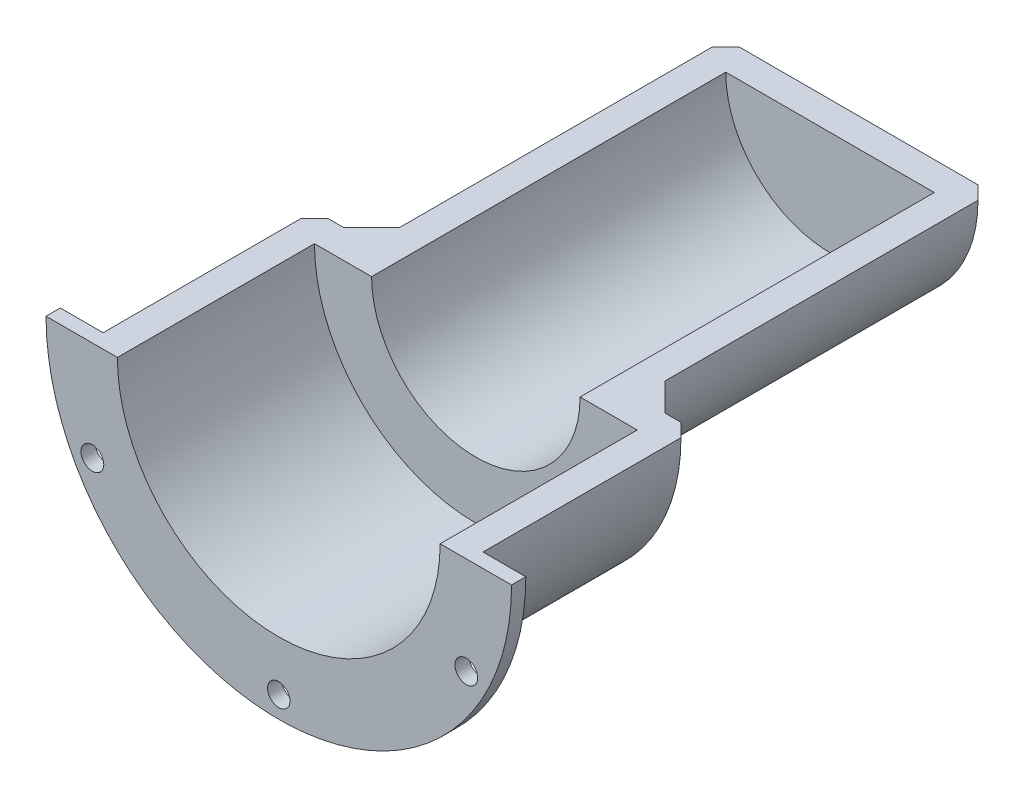
SolidWorks part; units mm, degrees
ref_plane "Front Plane" through (0, 0, 0) normal (0, 0, 1) x (1, 0, 0)
ref_plane "Top Plane" through (0, 0, 0) normal (0, 1, 0) x (1, 0, 0)
ref_plane "Right Plane" through (0, 0, 0) normal (1, 0, 0) x (0, 0, -1)
sketch "Sketch2" plane through (0, 0, 0) normal (0, 0, 1) x (1, 0, 0)
  line L0 (-23.622, 0) -> (23.622, 0) construction
  line L1 (-23.622, 0) -> (23.622, 0)
  arc A0 (-23.622, 0) -> (23.622, 0) centre (0, 0) ccw
  arc A1 (-18.542, 0) -> (18.542, 0) centre (0, 0) ccw
  arc A2 (18.542, 0) -> (-18.542, 0) centre (0, 0) ccw construction
  arc A3 (23.622, 0) -> (-23.622, 0) centre (0, 0) ccw construction
  dimension "D1" = 47.244
extrude "Boss-Extrude1" add sketch "Sketch2" against normal blind 62.992 contours A1 L1 A0
sketch "Sketch3" plane through (0, 0, 0) normal (0, 0, 1) x (1, 0, 0)
  line L0 (-23.622, 0) -> (23.622, 0) construction
  line L1 (-18.542, 0) -> (18.542, 0)
  arc A0 (-18.542, 0) -> (18.542, 0) centre (0, 0) ccw
extrude "Cut-Extrude1" cut sketch "Sketch3" against normal blind 57.912
sketch "Sketch5" plane through (0, 0, 0) normal (0, 0, 1) x (1, 0, 0)
  line L0 (-33.782, 0) -> (33.782, 0)
  arc A0 (-33.782, 0) -> (33.782, 0) centre (0, 0) ccw
extrude "Boss-Extrude2" add sketch "Sketch5" along normal blind 40.132
sketch "Sketch6" plane through (0, 0, 40.132) normal (0, 0, 1) x (1, 0, 0)
  line L0 (33.782, 0) -> (-33.782, 0) construction
  line L1 (-18.542, 0) -> (18.542, 0)
  arc A0 (-18.542, 0) -> (18.542, 0) centre (0, 0) ccw
extrude "Cut-Extrude2" cut sketch "Sketch6" against normal blind 40.132
sketch "Sketch7" plane through (0, 0, 40.132) normal (0, 0, 1) x (1, 0, 0)
  line L0 (-18.542, 0) -> (-33.782, 0) construction
  line L1 (33.782, 0) -> (18.542, 0) construction
  line L2 (-28.702, 0) -> (28.702, 0)
  arc A0 (-28.702, 0) -> (28.702, 0) centre (0, 0) ccw
extrude "Cut-Extrude3" cut sketch "Sketch7" against normal blind 35.052
sketch "Sketch9" plane through (0, 0, 40.132) normal (0, 0, 1) x (1, 0, 0)
  line L0 (-41.402, 0) -> (41.402, 0)
  arc A0 (-41.402, 0) -> (41.402, 0) centre (0, 0) ccw
extrude "Boss-Extrude3" add sketch "Sketch9" against normal blind 2.54
sketch "Sketch10" plane through (0, 0, 40.132) normal (0, 0, 1) x (1, 0, 0)
  line L0 (41.402, 0) -> (-41.402, 0) construction
  line L1 (-28.702, 0) -> (28.702, 0)
  arc A0 (-28.702, 0) -> (28.702, 0) centre (0, 0) ccw
extrude "Cut-Extrude4" cut sketch "Sketch10" against normal blind 2.54
chamfer "Chamfer1" distance 4.92 angle 45 1 edges at (0, -23.622, 0)
chamfer "Chamfer3" distance 2.38 angle 45 1 edges at (0, -23.622, -62.992)
chamfer "Chamfer4" distance 2.38 angle 45 1 edges at (0, -33.782, 0)
sketch "Sketch12" plane through (0, 0, 37.592) normal (0, 0, -1) x (-1, 0, 0)
  circle A0 centre (0, -37.592) radius 2
  arc A2 (-33.782, 0) -> (33.782, 0) centre (0, 0) ccw construction
  point P12 (0, -33.782)
  dimension "D1" = 3.81
  dimension "D2" = 4
extrude "Cut-Extrude6" cut sketch "Sketch12" against normal blind 2.54
sketch "Sketch16" plane through (0, 0, 40.132) normal (0, 0, 1) x (1, 0, 0)
  circle A0 centre (-33.1564, -17.7147) radius 2.032
  circle A1 centre (33.3594, -17.3294) radius 2.032
  arc A2 (-41.402, 0) -> (41.402, 0) centre (0, 0) ccw construction
  dimension "D1" = 37.592
  dimension "D2" = 37.592
extrude "Cut-Extrude7" cut sketch "Sketch16" against normal blind 2.54
